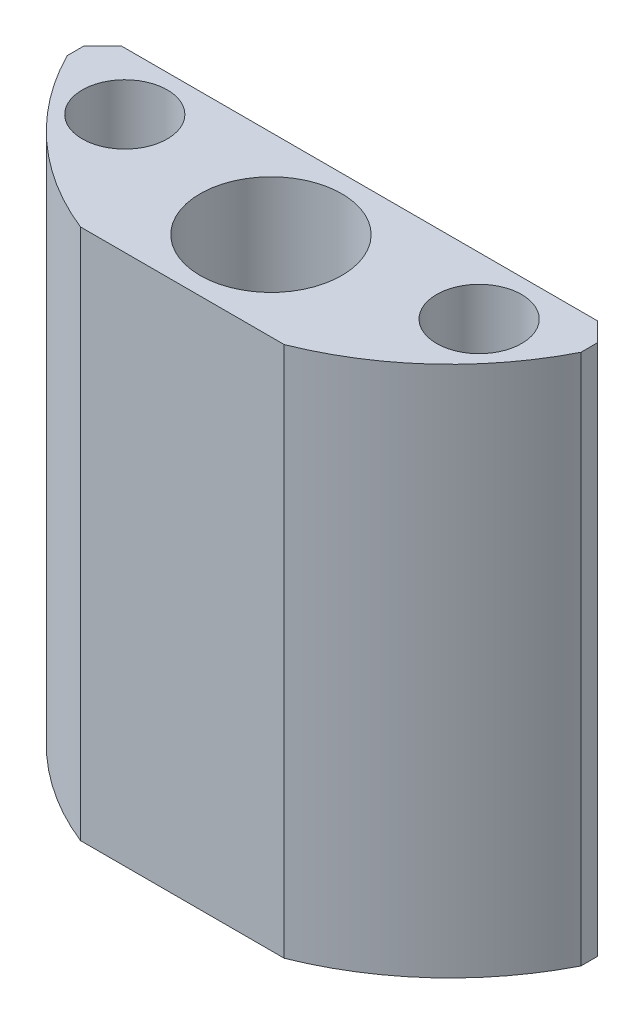
SolidWorks part; units mm, degrees
material "Copper"
ref_plane "Front Plane" through (0, 0, 0) normal (0, 0, 1) x (1, 0, 0)
ref_plane "Top Plane" through (0, 0, 0) normal (0, 1, 0) x (1, 0, 0)
ref_plane "Right Plane" through (0, 0, 0) normal (1, 0, 0) x (0, 0, -1)
sketch "Sketch1" plane through (0, 0, 0) normal (0, 1, 0) x (1, 0, 0)
  line L0 (-26.8787, 0) -> (26.8787, 0)
  line L1 (11.5, -20) -> (-11.5, -20)
  line L2 (-26.8787, 0) -> (-29, -2.1213)
  line L3 (-29, -4) -> (-29, 2.5234) construction
  line L4 (-29, -2.1213) -> (-29, -4)
  line L5 (0, 0) -> (0, -20) construction
  line L6 (29, -2.1213) -> (29, -4)
  line L7 (26.8787, 0) -> (29, -2.1213)
  arc A0 (-29, -4) -> (-11.5, -20) centre (0.8918, 11.1238) ccw
  arc A4 (29, -4) -> (11.5, -20) centre (-0.8918, 11.1238) cw
  dimension "D1" = 29
  dimension "D2" = 33.5
  dimension "D3" = 4
  dimension "D4" = 45
  dimension "D5" = 20
  dimension "D6" = 11.5
  dimension "D7" = 11.1238
  dimension "D8" = 3
extrude "Boss-Extrude1" add sketch "Sketch1" against normal blind 60
sketch "Sketch2" plane through (0, 0, 0) normal (0, 1, 0) x (1, 0, 0)
  line L0 (26.8787, 0) -> (-26.8787, 0) construction
  circle A0 centre (-20, -6.5) radius 4
  circle A1 centre (0, -10) radius 8
  circle A2 centre (20, -6.5) radius 4
  dimension "D1" = 8
  dimension "D5" = 16
  dimension "D6" = 8
  dimension "D2" = 20
  dimension "D3" = 6.5
  dimension "D4" = 10
  dimension "D7" = 20
  dimension "D8" = 6.5
extrude "Cut-Extrude1" cut sketch "Sketch2" against normal through all
sketch "Sketch3" plane through (0, 0, 0) normal (0, 1, 0) x (1, 0, 0)
  circle A0 centre (-20, -6.5) radius 4.8
  circle A1 centre (20, -6.5) radius 4.8
  dimension "D1" = 9.6
  dimension "D2" = 9.6
extrude "Cut-Extrude2" cut sketch "Sketch3" against normal blind 48
